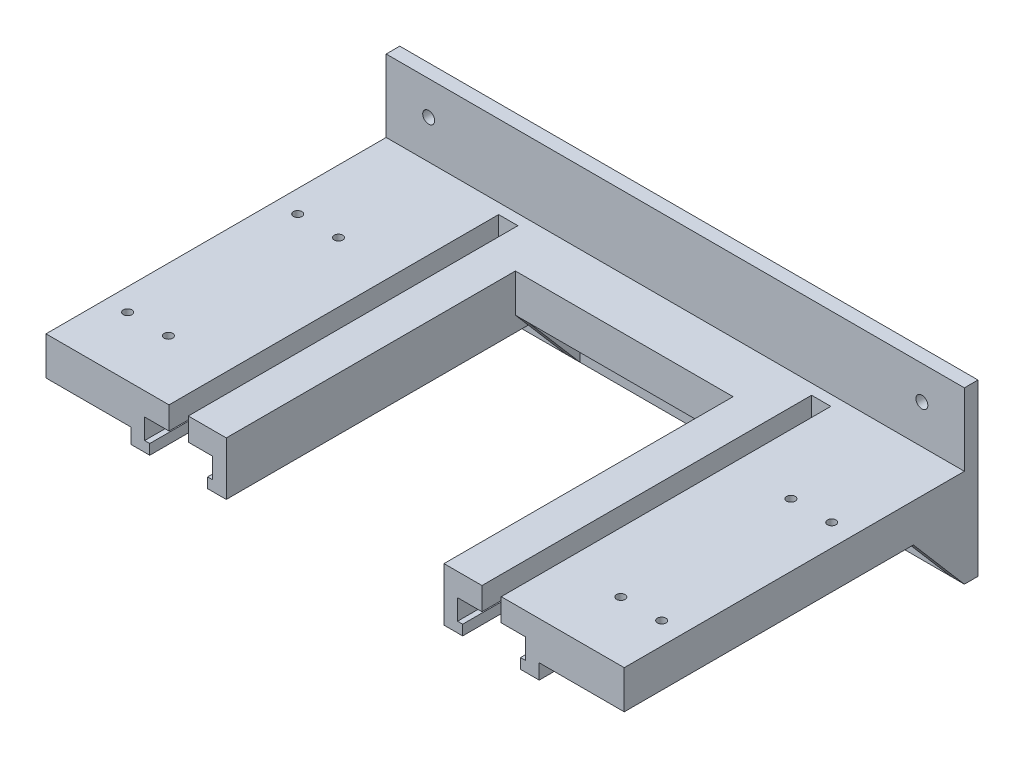
SolidWorks part; units mm, degrees
ref_plane "Alzado" through (0, 0, 0) normal (0, 0, 1) x (1, 0, 0)
ref_plane "Planta" through (0, 0, 0) normal (0, 1, 0) x (1, 0, 0)
ref_plane "Vista lateral" through (0, 0, 0) normal (1, 0, 0) x (0, 0, -1)
sketch "Croquis1" plane through (0, 0, 0) normal (0, 0, 1) x (1, 0, 0)
  line L1 (-85, 25) -> (85, 25)
  line L2 (-85, 25) -> (-85, -25)
  line L3 (-85, -25) -> (85, -25)
  line L4 (85, 25) -> (85, -25)
  line L5 (-85, 25) -> (85, -25) construction
  line L6 (-85, -25) -> (85, 25) construction
  point P0 (0, 0)
  dimension "D1" = 170
  dimension "D2" = 50
extrude "Saliente-Extruir1" add sketch "Croquis1" along normal blind 4
sketch "Croquis3" plane through (0, 0, 4) normal (0, 0, 1) x (1, 0, 0)
  line L0 (-85, 25) -> (-85, -25) construction
  line L2 (-85, 7.5) -> (85, 7.5)
  line L4 (-60, -11.9212) -> (-56, -11.9212)
  line L6 (-60, -7.5) -> (-85, -7.5)
  line L7 (-47.748, 25) -> (-47.748, 7.5) construction
  line L8 (85, 25) -> (-85, 25) construction
  line L9 (-47.748, 7.5) -> (-47.748, 25) construction
  line L10 (-56, -2.9212) -> (-56, -8.9212)
  line L11 (-85, -25) -> (85, -25) construction
  line L13 (-60, -7.5) -> (-60, -11.9212)
  line L17 (-32, -11.9212) -> (-32, -7.5)
  line L19 (32, -7.5) -> (32, -11.9212)
  line L22 (-36, -11.9212) -> (-32, -11.9212)
  line L23 (32, -11.9212) -> (36, -11.9212)
  line L26 (56, -11.9212) -> (60, -11.9212)
  line L27 (60, -11.9212) -> (60, -7.5)
  line L30 (0, 25) -> (0, -25) construction
  line L31 (-56, -8.9212) -> (-54.5, -8.9212)
  line L32 (-54.5, -8.9212) -> (-54.5, -11.9212)
  line L33 (-54.5, -11.9212) -> (-56, -11.9212)
  line L34 (-36, -8.9212) -> (-37.5, -8.9212)
  line L35 (-37.5, -8.9212) -> (-37.5, -11.9212)
  line L36 (-37.5, -11.9212) -> (-36, -11.9212)
  line L37 (37.5, -11.9212) -> (36, -11.9212)
  line L38 (37.5, -8.9212) -> (37.5, -11.9212)
  line L39 (36, -8.9212) -> (37.5, -8.9212)
  line L40 (56, -8.9212) -> (54.5, -8.9212)
  line L41 (54.5, -11.9212) -> (56, -11.9212)
  line L42 (54.5, -8.9212) -> (54.5, -11.9212)
  line L43 (85, -7.5) -> (60, -7.5)
  line L46 (85, 7.5) -> (85, -7.5)
  line L47 (-85, 7.5) -> (-85, -7.5)
  line L49 (-56, -2.9212) -> (-36, -2.9212)
  line L52 (56, -2.9212) -> (36, -2.9212)
  line L54 (32, -7.5) -> (-32, -7.5)
  line L55 (-36, -2.9212) -> (-36, -8.9212)
  line L56 (36, -2.9212) -> (36, -8.9212)
  line L57 (56, -2.9212) -> (56, -8.9212)
  line L58 (-85, 0) -> (85, 0) construction
  point P50 (0, -10.136)
  dimension "D1" = 4
  dimension "D2" = 3
  dimension "D3" = 6
  dimension "D4" = 1.5
  dimension "D5" = 15
  dimension "D6" = 20
  dimension "D7" = 25
extrude "Saliente-Extruir2" add sketch "Croquis3" along normal blind 100
sketch "Croquis4" plane through (-85, 0, 0) normal (-1, 0, 0) x (0, 0, 1)
  line L0 (4, -25) -> (19, -7.5)
  line L1 (104, -7.5) -> (4, -7.5) construction
  line L2 (19, -7.5) -> (4, -7.5)
  line L3 (4, -7.5) -> (4, -25)
  line L4 (0, 0) -> (104, 0) construction
  line L5 (104, 7.5) -> (104, -7.5) construction
  dimension "D1" = 15
extrude "Saliente-Extruir3" add sketch "Croquis4" against normal blind 25
sketch "Croquis5" plane through (32, 0, 0) normal (-1, 0, 0) x (0, 0, 1)
  line L0 (19, -7.5) -> (4, -25)
  line L1 (4, -25) -> (4, -7.5)
  line L2 (4, -7.5) -> (19, -7.5)
extrude "Saliente-Extruir4" add sketch "Croquis5" along normal up to surface (64 mm away) up to face at (-32, -9.7106, 54)
ref_plane "Plano1" through (60, -11.9212, 4) normal (0, 0, -1) x (-1, 0, 0)
sketch "Croquis7" plane through (60, 0, 0) normal (1, 0, 0) x (0, 0, -1)
  line L0 (-4, -25) -> (-19, -7.5)
  line L1 (-4, -28.0883) -> (-4, 4.2459) construction
  line L2 (-4, -25) -> (-15.2104, -11.9212) construction
  line L3 (-104, -7.5) -> (-4, -7.5) construction
  line L4 (-19, -7.5) -> (-4, -7.5)
  line L5 (-104, -7.5) -> (-4, -7.5) construction
  line L6 (-4, -7.5) -> (-4, -25)
  dimension "D1" = 15
extrude "Saliente-Extruir5" add sketch "Croquis7" along normal blind 25
sketch "Croquis9" plane through (0, 0, 104) normal (0, 0, 1) x (1, 0, 0)
  line L0 (-60, -7.5) -> (-85, -7.5) construction
  line L1 (-81, -7.5) -> (-64, -7.5)
  line L2 (-81, -7.5) -> (-81, -25)
  line L3 (-81, -25) -> (-64, -25)
  line L4 (-64, -7.5) -> (-64, -25)
  line L5 (-85, -25) -> (-60, -25) construction
  line L6 (-32, -7.5) -> (32, -7.5) construction
  line L8 (-28, -7.5) -> (-28, -25)
  line L11 (-32, -25) -> (32, -25) construction
  line L12 (60, -7.5) -> (85, -7.5) construction
  line L16 (28, -7.5) -> (28, -25)
  line L17 (64, -7.5) -> (81, -7.5)
  line L18 (64, -7.5) -> (64, -25)
  line L19 (64, -25) -> (81, -25)
  line L20 (81, -7.5) -> (81, -25)
  line L21 (85, -25) -> (60, -25) construction
  line L22 (-81, -14.0076) -> (-85, -14.0076) construction
  line L23 (-85, -25) -> (-85, -7.5) construction
  line L24 (-64, -17.5204) -> (-60, -17.5204) construction
  line L25 (-60, -11.9212) -> (-60, -25) construction
  line L26 (-32, -20.3836) -> (-28, -20.3836) construction
  line L27 (-32, -25) -> (-32, -11.9212) construction
  line L28 (-28, -7.5) -> (28, -7.5)
  line L29 (28, -15.1674) -> (32, -15.1674) construction
  line L30 (32, -11.9212) -> (32, -25) construction
  line L31 (60, -17.5204) -> (64, -17.5204) construction
  line L32 (60, -25) -> (60, -11.9212) construction
  line L33 (81, -12.1629) -> (85, -12.1629) construction
  line L34 (85, -7.5) -> (85, -25) construction
  line L35 (-28, -25) -> (28, -25)
  dimension "D1" = 4
extrude "Cortar-Extruir1" cut sketch "Croquis9" against normal blind 100
sketch "Croquis11" plane through (0, -7.5, 0) normal (0, -1, 0) x (1, 0, 0)
  line L0 (32, 104) -> (32, 15.2104) construction
  line L1 (-32, 104) -> (32, 104)
  line L2 (-32, 104) -> (-32, 19)
  line L3 (-32, 19) -> (32, 19)
  line L4 (32, 104) -> (32, 19)
  line L5 (-32, 19) -> (-28, 19) construction
extrude "Cortar-Extruir4" cut sketch "Croquis11" against normal blind 15
sketch "Croquis12" plane through (0, 0, 4) normal (0, 0, 1) x (1, 0, 0)
  line L0 (-72.5, 15.1385) -> (-74.25, 15.1385) construction
  line L1 (-72.5, 15.1385) -> (-70.75, 15.1385) construction
  line L2 (-72.5, 15.1385) -> (-72.5, 16.8885) construction
  line L4 (-72.5, 15.1385) -> (-72.5, -7.5) construction
  line L5 (-64, -7.5) -> (-81, -7.5) construction
  line L6 (-85, 0) -> (0, 0) construction
  line L7 (-85, 7.5) -> (-85, -7.5) construction
  line L8 (0, 0) -> (0, 13.3885) construction
  line L9 (0, 15.1385) -> (72.5, 15.1385) construction
  line L10 (-72.5, -15.1385) -> (72.5, -15.1385) construction
  circle A0 centre (-72.5, 15.1385) radius 1.75
  circle A1 centre (-72.5, -15.1385) radius 1.75
  circle A2 centre (72.5, -15.1385) radius 1.75
  circle A3 centre (72.5, 15.1385) radius 1.75
  dimension "D1" = 3.5
extrude "Cortar-Extruir5" cut sketch "Croquis12" against normal blind 15
sketch "Croquis14" plane through (-85, 0, 0) normal (-1, 0, 0) x (0, 0, 1)
  line L0 (19, -7.5) -> (4, -7.5)
  line L1 (4, 4.2459) -> (4, -28.0883) construction
  line L2 (4, -7.5) -> (4, -25)
  line L3 (4, -25) -> (19, -7.5)
extrude "Cortar-Extruir6" cut sketch "Croquis14" against normal blind 1
sketch "Croquis15" plane through (0, 0, 19) normal (0, 0, 1) x (1, 0, 0)
  line L0 (-32, 0) -> (32, 0)
  line L1 (32, 7.5) -> (32, -7.5) construction
  point P7 (0, 0)
ref_plane "Plano3" through (0, 0, 0) normal (0, -1, 0) x (1, 0, 0)
sketch "Croquis16" plane through (0, 0, 104) normal (0, 0, 1) x (1, 0, 0)
  line L0 (85, -7.5) -> (85, 7.5) construction
  line L1 (-85, 7.5) -> (85, 7.5)
  line L2 (-85, 7.5) -> (-85, 3.7521)
  line L3 (-85, 3.7521) -> (85, 3.7521)
  line L4 (85, 7.5) -> (85, 3.7521)
extrude "Cortar-Extruir7" cut sketch "Croquis16" against normal blind 100
sketch "Croquis20" plane through (0, -7.5, 0) normal (0, -1, 0) x (1, 0, 0)
  line L0 (-85, 86.5) -> (-60, 86.5) construction
  line L1 (-85, 104) -> (-85, 4) construction
  line L2 (-60, 104) -> (-60, 19) construction
  line L3 (-60, 86.5) -> (-60, 36.5) construction
  line L4 (-60, 104) -> (-60, 15.2104) construction
  line L5 (-60, 36.5) -> (-85, 36.5) construction
  line L6 (-60, 36.5) -> (-60, 19) construction
  line L7 (-85, 86.5) -> (-85, 104) construction
  line L8 (-72.5, 104) -> (-72.5, 36.5) construction
  line L9 (-85, 104) -> (-60, 104) construction
  line L10 (-85, 61.5) -> (-60, 61.5) construction
  line L11 (-78.5, 86.5) -> (-72.5, 86.5) construction
  line L12 (0, 0) -> (0, 104) construction
  circle A0 centre (-78.5, 86.5) radius 1.25
  circle A1 centre (-66.5, 86.5) radius 1.25
  circle A2 centre (-66.5, 36.5) radius 1.25
  circle A3 centre (-78.5, 36.5) radius 1.25
  circle A4 centre (66.5, 36.5) radius 1.25
  circle A5 centre (78.5, 36.5) radius 1.25
  circle A6 centre (66.5, 86.5) radius 1.25
  circle A7 centre (78.5, 86.5) radius 1.25
  dimension "D2" = 2.5
  dimension "D3" = 12
  dimension "D1" = 50
  dimension "D4" = 6
  dimension "D5" = 50
extrude "Cortar-Extruir10" cut sketch "Croquis20" against normal through all both and the other way through all
sketch "Croquis21" plane through (0, -2.9212, 0) normal (0, -1, 0) x (1, 0, 0)
  line L0 (-56, 104) -> (-36, 104) construction
  line L1 (-48.8333, 104) -> (-43.1667, 104)
  line L2 (-48.8333, 104) -> (-48.8333, 7.1003)
  line L3 (-48.8333, 7.1003) -> (-43.1667, 7.1003)
  line L4 (-43.1667, 104) -> (-43.1667, 7.1003)
  line L5 (-48.8333, 94.022) -> (-54.5, 94.022) construction
  line L6 (-54.5, 104) -> (-54.5, 4) construction
  line L7 (-54.5, 94.022) -> (-37.5, 77.022) construction
  line L8 (-37.5, 104) -> (-37.5, 4) construction
  line L9 (-37.5, 77.022) -> (-43.1667, 77.022) construction
  line L10 (0, 0) -> (0, 104) construction
  line L11 (48.8333, 7.1003) -> (43.1667, 7.1003)
  line L12 (43.1667, 104) -> (43.1667, 7.1003)
  line L13 (48.8333, 104) -> (43.1667, 104)
  line L14 (48.8333, 104) -> (48.8333, 7.1003)
extrude "Cortar-Extruir11" cut sketch "Croquis21" against normal blind 10
